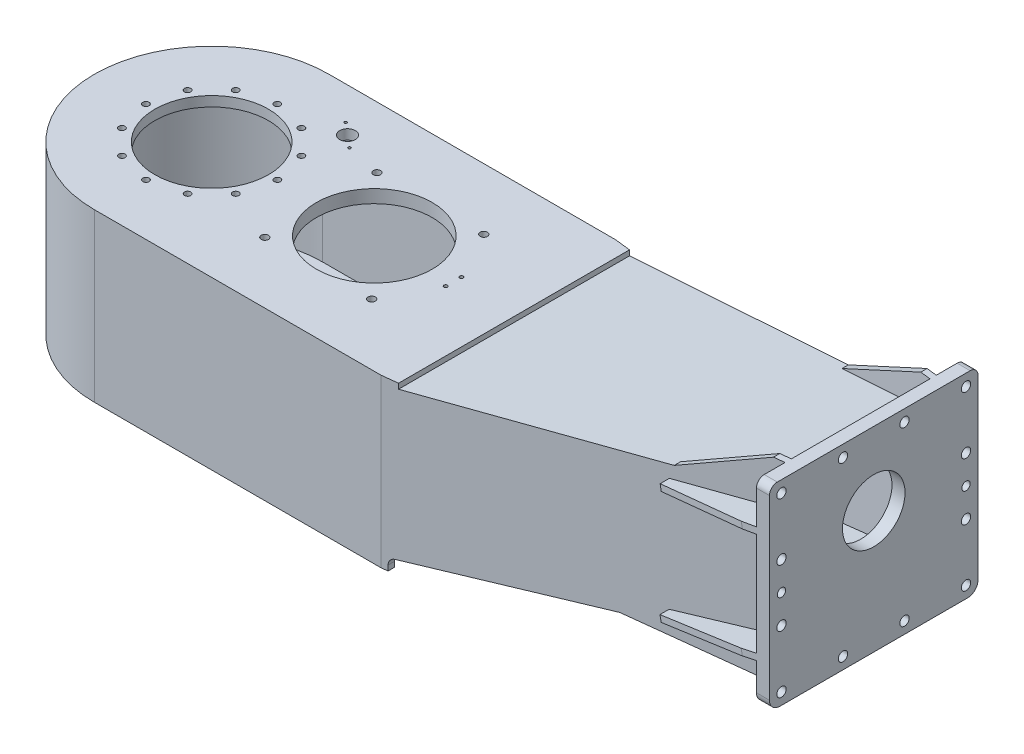
SolidWorks part; units mm, degrees
ref_plane "正面" through (0, 0, 0) normal (0, 0, 1) x (1, 0, 0)
ref_plane "平面" through (0, 0, 0) normal (0, 1, 0) x (1, 0, 0)
ref_plane "右側面" through (0, 0, 0) normal (1, 0, 0) x (0, 0, -1)
sketch "ｽｹｯﾁ1" plane through (0, 0, 0) normal (0, 1, 0) x (1, 0, 0)
  line L0 (1245, 145) -> (550, 225)
  line L1 (550, 225) -> (0, 225)
  line L2 (0, -225) -> (550, -225)
  line L3 (550, -225) -> (1245, -145)
  line L4 (1245, -145) -> (1245, -132.9388)
  line L5 (1245, -132.9388) -> (549.468, -213)
  line L6 (549.468, -213) -> (0, -213)
  line L7 (0, 213) -> (549.468, 213)
  line L8 (549.468, 213) -> (1245, 132.9388)
  line L9 (1245, 132.9388) -> (1245, 145)
  arc A0 (0, 225) -> (-225, 0) centre (0, 0) ccw
  arc A1 (-225, 0) -> (0, -225) centre (0, 0) ccw
  arc A2 (0, -213) -> (-213, 0) centre (0, 0) cw
  arc A3 (-213, 0) -> (0, 213) centre (0, 0) cw
extrude "ﾎﾞｽ - 押し出し1" add sketch "ｽｹｯﾁ1" along normal blind 482.5
sketch "ｽｹｯﾁ2" plane through (0, 0, 0) normal (0, 0, 1) x (1, 0, 0)
  line L0 (-240, 500) -> (-240, 320)
  line L1 (-240, 320) -> (580, 320)
  line L2 (580, 320) -> (580, 310)
  line L3 (580, 310) -> (1054.273, 393.309)
  line L4 (1054.273, 393.309) -> (1225, 482.5)
  line L5 (1225, 482.5) -> (1280, 482.5)
  line L6 (1280, 482.5) -> (1280, 500)
  line L7 (1280, 500) -> (-240, 500)
extrude "ｶｯﾄ - 押し出し1" cut sketch "ｽｹｯﾁ2" against normal through all and the other way through all
sketch "ｽｹｯﾁ3" plane through (0, 0, 0) normal (0, 0, 1) x (1, 0, 0)
  line L0 (562, -10) -> (1280, -10)
  line L1 (1280, -10) -> (1280, 107.5)
  line L2 (1280, 107.5) -> (960.501, 107.5)
  line L3 (960.501, 107.5) -> (574.315, 24.6797)
  line L4 (562, 9.922) -> (562, -10)
  arc A0 (574.315, 24.6797) -> (562, 9.922) centre (577, 9.922) ccw
extrude "ｶｯﾄ - 押し出し2" cut sketch "ｽｹｯﾁ3" against normal through all and the other way through all
ref_plane "平面1" through (0, 301, 0) normal (0, 1, 0) x (1, 0, 0)
ref_plane "平面2" through (0, 295, 0) normal (0, 1, 0) x (1, 0, 0)
sketch "ｽｹｯﾁ6" plane through (0, 301, 0) normal (0, 1, 0) x (1, 0, 0)
  line L0 (580, 221.5468) -> (550, 225)
  line L1 (550, 225) -> (0, 225)
  line L2 (0, -225) -> (550, -225)
  line L3 (550, -225) -> (580, -221.5468)
  line L4 (580, -221.5468) -> (580, 221.5468)
  arc A0 (0, 225) -> (-225, 0) centre (0, 0) ccw
  arc A1 (-225, 0) -> (0, -225) centre (0, 0) ccw
extrude "ﾎﾞｽ - 押し出し2" add sketch "ｽｹｯﾁ6" along normal blind 19
ref_plane "平面3" through (0, 301, 0) normal (0, 1, 0) x (1, 0, 0)
ref_plane "平面4" through (0, 295, 0) normal (0, 1, 0) x (1, 0, 0)
sketch "ｽｹｯﾁ9" plane through (0, 295, 0) normal (0, 1, 0) x (1, 0, 0)
  line L0 (175, -135) -> (475, -135)
  line L1 (475, -135) -> (475, 135)
  line L2 (475, 135) -> (175, 135)
  line L3 (175, 135) -> (175, -135)
extrude "ﾎﾞｽ - 押し出し3" add sketch "ｽｹｯﾁ9" along normal blind 7
sketch "ｽｹｯﾁ10" plane through (0, 0, 0) normal (0, 1, 0) x (1, 0, 0)
  line L0 (531, 225) -> (0, 225)
  line L1 (0, -225) -> (531, -225)
  line L2 (531, -225) -> (531, 225)
  line L3 (531, 173) -> (0, 173)
  line L4 (0, -173) -> (531, -173)
  line L5 (531, -173) -> (531, 173)
  arc A0 (0, 225) -> (-225, 0) centre (0, 0) ccw
  arc A1 (-225, 0) -> (0, -225) centre (0, 0) ccw
  arc A2 (0, 173) -> (-173, 0) centre (0, 0) ccw
  arc A3 (-173, 0) -> (0, -173) centre (0, 0) ccw
ref_plane "平面5" through (0, 301, 0) normal (0, 1, 0) x (1, 0, 0)
ref_plane "平面6" through (0, 295, 0) normal (0, 1, 0) x (1, 0, 0)
sketch "ｽｹｯﾁ13" plane through (0, 0, 0) normal (0, 1, 0) x (1, 0, 0)
  line L0 (531, 225) -> (0, 225)
  line L1 (0, -225) -> (531, -225)
  line L2 (531, -225) -> (531, -173)
  line L3 (531, -173) -> (0, -173)
  line L4 (0, 173) -> (531, 173)
  line L5 (531, 173) -> (531, 225)
  arc A0 (0, 225) -> (-225, 0) centre (0, 0) ccw
  arc A1 (-225, 0) -> (0, -225) centre (0, 0) ccw
  arc A2 (0, -173) -> (-173, 0) centre (0, 0) cw
  arc A3 (-173, 0) -> (0, 173) centre (0, 0) cw
extrude "ﾎﾞｽ - 押し出し5" add sketch "ｽｹｯﾁ13" along normal blind 14
ref_plane "平面7" through (531, 0, 0) normal (1, 0, 0) x (0, 0, -1)
sketch "ｽｹｯﾁ15" plane through (0, 0, 0) normal (0, 0, 1) x (1, 0, 0)
  line L0 (531, 0) -> (547, 0)
  line L1 (547, 0) -> (547, 301)
  line L2 (547, 301) -> (531, 301)
  line L3 (531, 301) -> (531, 0)
extrude "ﾎﾞｽ - 押し出し6" add sketch "ｽｹｯﾁ15" against normal blind 225 and the other way blind 225
sketch "ｽｹｯﾁ16" plane through (531, 0, 0) normal (1, 0, 0) x (0, 0, -1)
  line L0 (155, 99.5) -> (155, 201)
  line L1 (105, 251) -> (-105, 251)
  line L2 (-155, 201) -> (-155, 99.5)
  line L3 (-105, 49.5) -> (105, 49.5)
  arc A0 (155, 201) -> (105, 251) centre (105, 201) ccw
  arc A1 (-105, 251) -> (-155, 201) centre (-105, 201) ccw
  arc A2 (-155, 99.5) -> (-105, 49.5) centre (-105, 99.5) ccw
  arc A3 (105, 49.5) -> (155, 99.5) centre (105, 99.5) ccw
sketch "ｽｹｯﾁ17" plane through (531, 0, 0) normal (1, 0, 0) x (0, 0, -1)
  line L0 (155, 99.5) -> (155, 201)
  line L1 (105, 251) -> (-105, 251)
  line L2 (-155, 201) -> (-155, 99.5)
  line L3 (-105, 49.5) -> (105, 49.5)
  arc A0 (155, 201) -> (105, 251) centre (105, 201) ccw
  arc A1 (-105, 251) -> (-155, 201) centre (-105, 201) ccw
  arc A2 (-155, 99.5) -> (-105, 49.5) centre (-105, 99.5) ccw
  arc A3 (105, 49.5) -> (155, 99.5) centre (105, 99.5) ccw
extrude "ｶｯﾄ - 押し出し4" cut sketch "ｽｹｯﾁ17" along normal blind 16
sketch "ｽｹｯﾁ18" plane through (0, 0, 0) normal (0, 0, 1) x (1, 0, 0)
  line L0 (580, 297.8163) -> (1245, 414.6277)
  line L1 (1245, 414.6277) -> (1245, 426.8114)
  line L2 (1245, 426.8114) -> (580, 310)
  line L3 (580, 310) -> (580, 297.8163)
extrude "ﾎﾞｽ - 押し出し7" add sketch "ｽｹｯﾁ18" against normal blind 225 and the other way blind 225
sketch "ｽｹｯﾁ19" plane through (0, 0, 0) normal (0, 0, 1) x (1, 0, 0)
  line L0 (547, 18.83) -> (1245, 168.5095)
  line L1 (1245, 168.5095) -> (1245, 177.7141)
  line L2 (1245, 177.7141) -> (547, 28.0346)
  line L3 (547, 28.0346) -> (547, 18.83)
extrude "ﾎﾞｽ - 押し出し8" add sketch "ｽｹｯﾁ19" against normal blind 225 and the other way blind 225
sketch "ｽｹｯﾁ20" plane through (0, 0, 0) normal (0, 1, 0) x (1, 0, 0)
  line L0 (550, 225) -> (1250, 144.4245)
  line L1 (1250, 144.4245) -> (1250, 245)
  line L2 (1250, 245) -> (550, 245)
  line L3 (550, 245) -> (550, 225)
  line L4 (550, -225) -> (1250, -144.4245)
  line L5 (1250, -144.4245) -> (1250, -245)
  line L6 (1250, -245) -> (550, -245)
  line L7 (550, -245) -> (550, -225)
extrude "ｶｯﾄ - 押し出し5" cut sketch "ｽｹｯﾁ20" against normal through all and the other way through all
ref_plane "平面21" through (0, 301, 0) normal (0, 1, 0) x (1, 0, 0)
ref_plane "平面22" through (0, 295, 0) normal (0, 1, 0) x (1, 0, 0)
ref_plane "平面23" through (-41.5875, 236.7552, 0) normal (-0.173, 0.9849, 0) x (0.9849, 0.173, 0)
ref_plane "平面24" through (-29.339, 167.0249, 0) normal (-0.173, 0.9849, 0) x (0.9849, 0.173, 0)
sketch "ｽｹｯﾁ51" plane through (-29.339, 167.0249, 0) normal (-0.173, 0.9849, 0) x (0.9849, 0.173, 0)
  line L0 (1093.873, 161.6718) -> (1093.873, 185.6718)
  line L1 (1093.873, 185.6718) -> (1266.4757, 200)
  line L2 (1266.4757, 200) -> (1314.1557, 200)
  line L3 (1314.1557, 200) -> (1314.1557, 136.6978)
  line L4 (1314.1557, 136.6978) -> (1093.873, 161.6718)
  line L5 (1093.873, -161.6718) -> (1093.873, -185.6718)
  line L6 (1093.873, -185.6718) -> (1266.4757, -200)
  line L7 (1266.4757, -200) -> (1314.1557, -200)
  line L8 (1314.1557, -200) -> (1314.1557, -136.6978)
  line L9 (1314.1557, -136.6978) -> (1093.873, -161.6718)
extrude "ﾎﾞｽ - 押し出し22" add sketch "ｽｹｯﾁ51" along normal blind 12
ref_plane "平面25" through (22.7343, -106.0167, 0) normal (0.2097, -0.9778, 0) x (-0.9778, -0.2097, 0)
ref_plane "平面26" through (17.6406, -82.2633, 0) normal (0.2097, -0.9778, 0) x (-0.9778, -0.2097, 0)
sketch "ｽｹｯﾁ54" plane through (17.6406, -82.2633, 0) normal (0.2097, -0.9778, 0) x (-0.9778, -0.2097, 0)
  line L0 (-1053.8235, 161.6718) -> (-1053.8235, 185.6718)
  line L1 (-1053.8235, 185.6718) -> (-1227.6882, 200)
  line L2 (-1227.6882, 200) -> (-1275.7168, 200)
  line L3 (-1275.7168, 200) -> (-1275.7168, 136.6978)
  line L4 (-1275.7168, 136.6978) -> (-1053.8235, 161.6718)
  line L5 (-1053.8235, -161.6718) -> (-1053.8235, -185.6718)
  line L6 (-1053.8235, -185.6718) -> (-1227.6882, -200)
  line L7 (-1227.6882, -200) -> (-1275.7168, -200)
  line L8 (-1275.7168, -200) -> (-1275.7168, -136.6978)
  line L9 (-1275.7168, -136.6978) -> (-1053.8235, -161.6718)
extrude "ﾎﾞｽ - 押し出し23" add sketch "ｽｹｯﾁ54" against normal blind 12
ref_plane "平面27" through (1235, 0, 0) normal (1, 0, 0) x (0, 0, -1)
ref_plane "平面28" through (1245, 0, 0) normal (1, 0, 0) x (0, 0, -1)
sketch "ｽｹｯﾁ57" plane through (1235, 0, 0) normal (1, 0, 0) x (0, 0, -1)
  line L0 (134, 210) -> (143, 210)
  line L1 (143, 210) -> (143, 380)
  line L2 (143, 380) -> (134, 380)
  line L3 (134, 380) -> (134, 210)
  line L4 (-134, 210) -> (-143, 210)
  line L5 (-143, 210) -> (-143, 380)
  line L6 (-143, 380) -> (-134, 380)
  line L7 (-134, 380) -> (-134, 210)
extrude "ﾎﾞｽ - 押し出し24" add sketch "ｽｹｯﾁ57" along normal blind 35
sketch "ｽｹｯﾁ58" plane through (1245, 0, 0) normal (1, 0, 0) x (0, 0, -1)
  line L0 (200, 127.5) -> (200, 467.5)
  line L1 (185, 482.5) -> (-185, 482.5)
  line L2 (-200, 467.5) -> (-200, 127.5)
  line L3 (-180, 107.5) -> (180, 107.5)
  arc A0 (200, 467.5) -> (185, 482.5) centre (185, 467.5) ccw
  arc A1 (-185, 482.5) -> (-200, 467.5) centre (-185, 467.5) ccw
  arc A2 (-200, 127.5) -> (-180, 107.5) centre (-180, 127.5) ccw
  arc A3 (180, 107.5) -> (200, 127.5) centre (180, 127.5) ccw
extrude "ﾎﾞｽ - 押し出し25" add sketch "ｽｹｯﾁ58" along normal blind 25
sketch "ｽｹｯﾁ59" plane through (0, 301, 0) normal (0, 1, 0) x (1, 0, 0)
  circle A0 centre (0, 0) radius 109
extrude "ｶｯﾄ - 押し出し6" cut sketch "ｽｹｯﾁ59" against normal through all and the other way through all
sketch "ｽｹｯﾁ60" plane through (0, 301, 0) normal (0, 1, 0) x (1, 0, 0)
  circle A0 centre (126, 0) radius 6
  circle A1 centre (109.1192, 63) radius 6
  circle A2 centre (63, 109.1192) radius 6
  circle A3 centre (0, 126) radius 6
  circle A4 centre (-63, 109.1192) radius 6
  circle A5 centre (-109.1192, 63) radius 6
  circle A6 centre (-126, 0) radius 6
  circle A7 centre (-109.1192, -63) radius 6
  circle A8 centre (-63, -109.1192) radius 6
  circle A9 centre (0, -126) radius 6
  circle A10 centre (63, -109.1192) radius 6
  circle A11 centre (109.1192, -63) radius 6
extrude "ｶｯﾄ - 押し出し7" cut sketch "ｽｹｯﾁ60" against normal through all and the other way through all
sketch "ｽｹｯﾁ61" plane through (0, 301, 0) normal (0, 1, 0) x (1, 0, 0)
  circle A0 centre (118.93, 141.718) radius 15
extrude "ｶｯﾄ - 押し出し8" cut sketch "ｽｹｯﾁ61" against normal through all and the other way through all
sketch "ｽｹｯﾁ62" plane through (0, 301, 0) normal (0, 1, 0) x (1, 0, 0)
  circle A0 centre (141.898, 122.435) radius 2.5
  circle A1 centre (95.935, 161.002) radius 2.5
extrude "ｶｯﾄ - 押し出し9" cut sketch "ｽｹｯﾁ62" against normal through all and the other way through all
sketch "ｽｹｯﾁ63" plane through (0, 295, 0) normal (0, 1, 0) x (1, 0, 0)
  circle A0 centre (312, 0) radius 111
extrude "ｶｯﾄ - 押し出し10" cut sketch "ｽｹｯﾁ63" against normal through all and the other way through all
sketch "ｽｹｯﾁ64" plane through (0, 295, 0) normal (0, 1, 0) x (1, 0, 0)
  circle A0 centre (209.5, 107.5) radius 7
  circle A1 centre (209.5, -107.5) radius 7
  circle A2 centre (414.5, 107.5) radius 7
  circle A3 centre (414.5, -107.5) radius 7
extrude "ｶｯﾄ - 押し出し11" cut sketch "ｽｹｯﾁ64" against normal through all and the other way through all
sketch "ｽｹｯﾁ65" plane through (0, 295, 0) normal (0, 1, 0) x (1, 0, 0)
  circle A0 centre (464, 15) radius 3.4
  circle A1 centre (464, -15) radius 3.4
extrude "ｶｯﾄ - 押し出し12" cut sketch "ｽｹｯﾁ65" against normal through all and the other way through all
sketch "ｽｹｯﾁ66" plane through (1245, 0, 0) normal (1, 0, 0) x (0, 0, -1)
  circle A0 centre (177, 130) radius 9
  circle A1 centre (177, 240) radius 9
  circle A2 centre (177, 350) radius 9
  circle A3 centre (177, 460) radius 9
  circle A4 centre (-177, 130) radius 9
  circle A5 centre (-177, 240) radius 9
  circle A6 centre (-177, 350) radius 9
  circle A7 centre (-177, 460) radius 9
  circle A8 centre (59, 130) radius 9
  circle A9 centre (59, 460) radius 9
  circle A10 centre (-59, 130) radius 9
  circle A11 centre (-59, 460) radius 9
sketch "ｽｹｯﾁ67" plane through (1245, 0, 0) normal (1, 0, 0) x (0, 0, -1)
  circle A0 centre (177, 130) radius 9
  circle A1 centre (177, 240) radius 9
  circle A2 centre (177, 350) radius 9
  circle A3 centre (177, 460) radius 9
  circle A4 centre (-177, 130) radius 9
  circle A5 centre (-177, 240) radius 9
  circle A6 centre (-177, 350) radius 9
  circle A7 centre (-177, 460) radius 9
  circle A8 centre (59, 130) radius 9
  circle A9 centre (59, 460) radius 9
  circle A10 centre (-59, 130) radius 9
  circle A11 centre (-59, 460) radius 9
extrude "ｶｯﾄ - 押し出し14" cut sketch "ｽｹｯﾁ67" along normal blind 25
sketch "ｽｹｯﾁ68" plane through (1245, 0, 0) normal (1, 0, 0) x (0, 0, -1)
  circle A0 centre (177, 295) radius 8
  circle A1 centre (-177, 295) radius 8
sketch "ｽｹｯﾁ69" plane through (1245, 0, 0) normal (1, 0, 0) x (0, 0, -1)
  circle A0 centre (177, 295) radius 8
  circle A1 centre (-177, 295) radius 8
extrude "ｶｯﾄ - 押し出し16" cut sketch "ｽｹｯﾁ69" along normal blind 25
sketch "ｽｹｯﾁ70" plane through (1245, 0, 0) normal (1, 0, 0) x (0, 0, -1)
  circle A0 centre (0, 342.5) radius 60
sketch "ｽｹｯﾁ71" plane through (1245, 0, 0) normal (1, 0, 0) x (0, 0, -1)
  circle A0 centre (0, 342.5) radius 60
extrude "ｶｯﾄ - 押し出し18" cut sketch "ｽｹｯﾁ71" along normal blind 25
